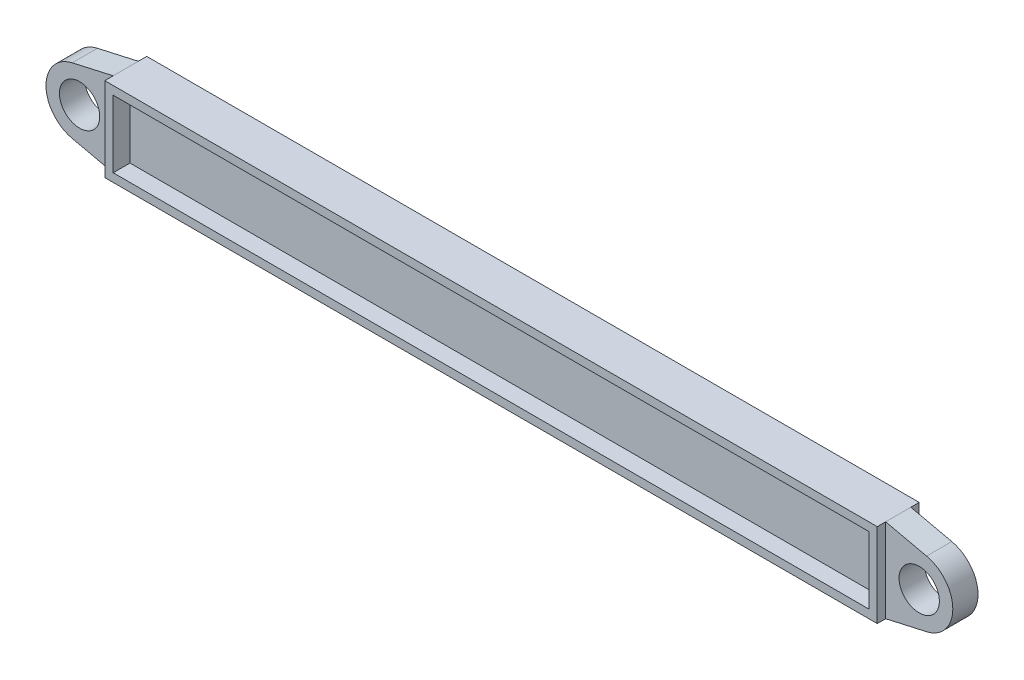
SolidWorks part; units mm, degrees
ref_plane "前视基准面" through (0, 0, 0) normal (0, 0, 1) x (1, 0, 0)
ref_plane "上视基准面" through (0, 0, 0) normal (0, 1, 0) x (1, 0, 0)
ref_plane "右视基准面" through (0, 0, 0) normal (1, 0, 0) x (0, 0, -1)
sketch "草图1" plane through (0, 0, 0) normal (0, 0, 1) x (1, 0, 0)
  line L0 (0, 20) -> (500, 20) construction
  line L5 (20, 45) -> (-4.3902, 39.5122)
  line L6 (250, 0) -> (250, 40) construction
  line L7 (480, 45) -> (504.3902, 39.5122)
  line L8 (20, 45) -> (480, 45)
  line L9 (20, -5) -> (480, -5)
  line L10 (480, -5) -> (504.3902, 0.4878)
  line L11 (20, -5) -> (-4.3902, 0.4878)
  arc A0 (-4.3902, 39.5122) -> (-4.3902, 0.4878) centre (0, 20) ccw
  circle A1 centre (0, 20) radius 12
  arc A2 (504.3902, 39.5122) -> (504.3902, 0.4878) centre (500, 20) cw
  circle A3 centre (500, 20) radius 12
extrude "凸台-拉伸1" add sketch "草图1" along normal blind 25
sketch "草图2" plane through (0, 0, 25) normal (0, 0, 1) x (1, 0, 0)
  line L0 (-4.3902, 39.5122) -> (20, 45)
  line L1 (20, 45) -> (20, -5)
  line L2 (20, -5) -> (-4.3902, 0.4878)
  line L3 (504.3902, 39.5122) -> (480, 45)
  line L4 (480, 45) -> (480, -5)
  line L5 (480, -5) -> (504.3902, 0.4878)
  arc A0 (-4.3902, 39.5122) -> (-4.3902, 0.4878) centre (0, 20) ccw
  arc A1 (504.3902, 0.4878) -> (504.3902, 39.5122) centre (500, 20) ccw
extrude "切除-拉伸1" cut sketch "草图2" against normal blind 5
sketch "草图4" plane through (0, 0, 0) normal (0, 0, -1) x (-1, 0, 0)
  line L1 (-480, -5) -> (-532.5638, -5)
  line L2 (-480, -5) -> (-480, 71.237)
  line L3 (-480, 71.237) -> (-532.5638, 71.237)
  line L4 (-532.5638, -5) -> (-532.5638, 71.237)
  line L5 (-20, -5) -> (37.7672, -5)
  line L6 (-20, -5) -> (-20, 88.7211)
  line L7 (-20, 88.7211) -> (37.7672, 88.7211)
  line L8 (37.7672, -5) -> (37.7672, 88.7211)
extrude "切除-拉伸5" cut sketch "草图4" against normal blind 5
sketch "草图5" plane through (0, 0, 0) normal (0, 0, -1) x (-1, 0, 0)
  line L0 (-480, 45) -> (-20, 45) construction
  line L1 (-475, 40) -> (-25, 40)
  line L2 (-475, 40) -> (-475, 0)
  line L3 (-475, 0) -> (-25, 0)
  line L4 (-25, 40) -> (-25, 0)
  line L5 (-20, 45) -> (-20, -5) construction
  dimension "D1" = 450
  dimension "D2" = 40
  dimension "D3" = 5
  dimension "D4" = 5
extrude "切除-拉伸6" cut sketch "草图5" against normal blind 10
sketch "草图7" plane through (0, 0, 25) normal (0, 0, 1) x (1, 0, 0)
  line L0 (25, 40) -> (475, 40)
  line L1 (25, 40) -> (25, 0)
  line L2 (25, 0) -> (475, 0)
  line L3 (475, 40) -> (475, 0)
extrude "切除-拉伸7" cut sketch "草图7" against normal blind 10
